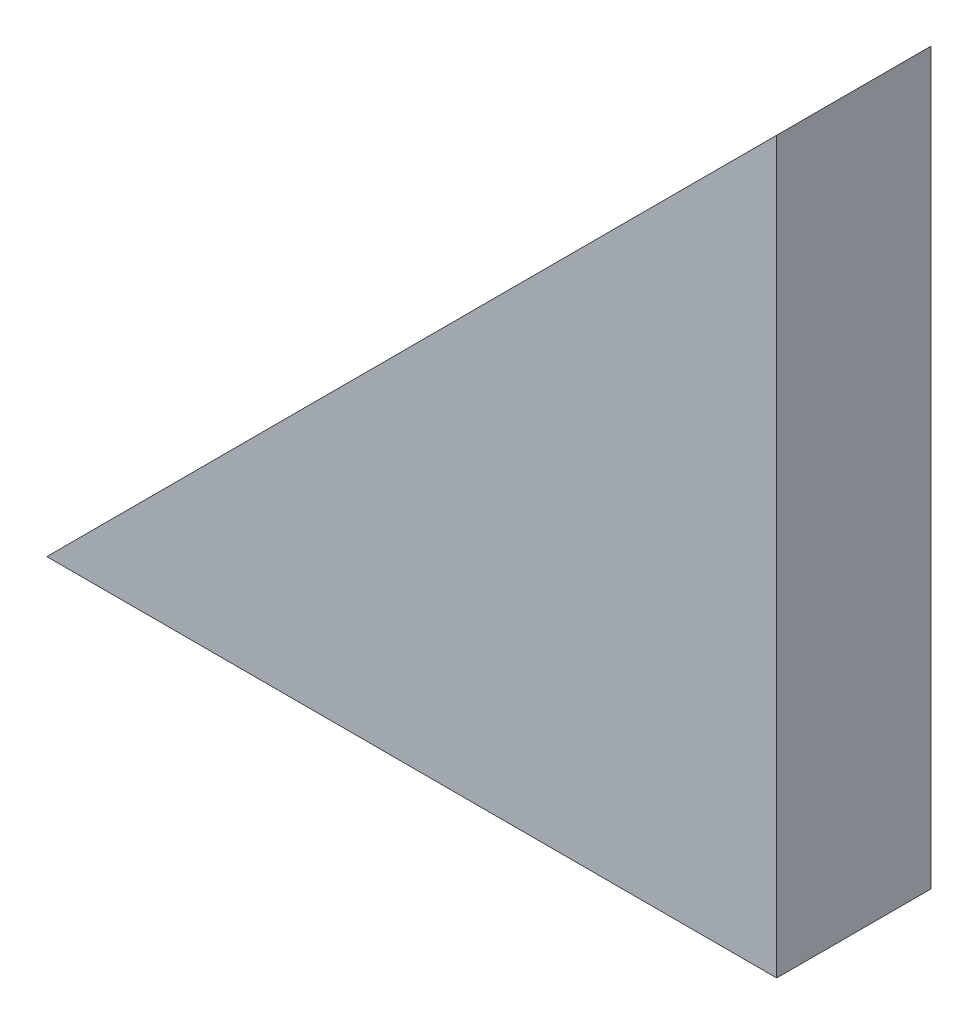
SolidWorks part; units mm, degrees
ref_plane "Alzado" through (0, 0, 0) normal (0, 0, 1) x (1, 0, 0)
ref_plane "Planta" through (0, 0, 0) normal (0, 1, 0) x (1, 0, 0)
ref_plane "Vista lateral" through (0, 0, 0) normal (1, 0, 0) x (0, 0, -1)
sketch "Croquis1" plane through (0, 0, 0) normal (0, 0, 1) x (1, 0, 0)
  line L0 (0, 0) -> (-45, 0)
  line L1 (0, 0) -> (0, 45)
  line L2 (0, 45) -> (-45, 0)
  dimension "D1" = 45
  dimension "D2" = 45
extrude "Saliente-Extruir1" add sketch "Croquis1" along normal blind 9.525
